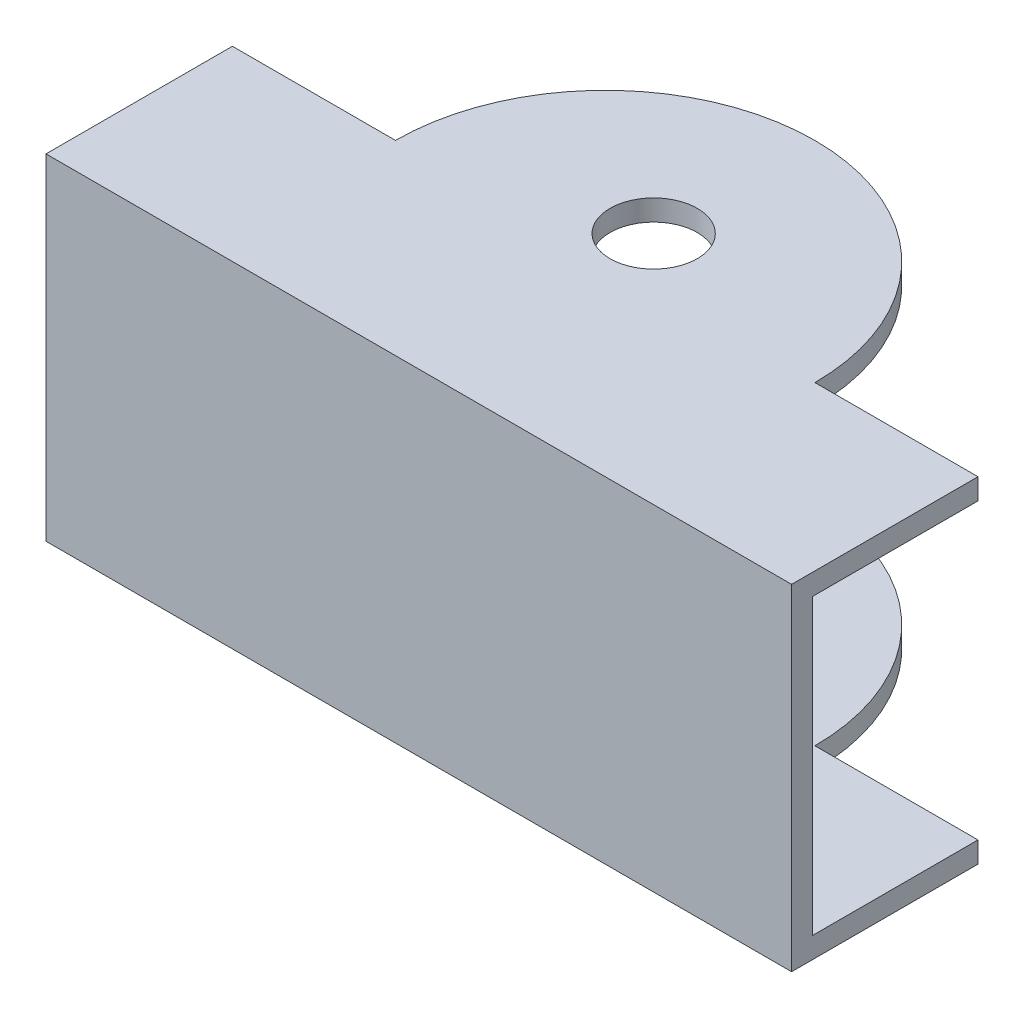
SolidWorks part; units mm, degrees
material "6061 Alloy"
ref_plane "Front Plane" through (0, 0, 0) normal (0, 0, 1) x (1, 0, 0)
ref_plane "Top Plane" through (0, 0, 0) normal (0, 1, 0) x (1, 0, 0)
ref_plane "Right Plane" through (0, 0, 0) normal (1, 0, 0) x (0, 0, -1)
sketch "Sketch1" plane through (0, 0, 0) normal (0, 1, 0) x (1, 0, 0)
  line L0 (0, 0) -> (28.2222, 0)
  line L1 (28.2222, 0) -> (28.2222, 14.1111)
  line L2 (28.2222, 14.1111) -> (15.875, 14.1111)
  line L3 (0, 0) -> (-28.2222, 0)
  line L4 (-28.2222, 0) -> (-28.2222, 14.1111)
  line L5 (-28.2222, 14.1111) -> (-15.875, 14.1111)
  arc A0 (-15.875, 14.1111) -> (15.875, 14.1111) centre (0, 14.1111) cw
  point P9 (0, 29.9861)
  dimension "D1" = 15.875
extrude "Boss-Extrude2" add sketch "Sketch1" along normal blind 25.4
sketch "Sketch3" plane through (28.2222, 0, 0) normal (1, 0, 0) x (0, 0, -1)
  line L0 (0, 25.4) -> (14.1111, 25.4) construction
  line L1 (1.5875, 23.8125) -> (62.6533, 23.8125)
  line L2 (1.5875, 23.8125) -> (1.5875, 1.5875)
  line L3 (1.5875, 1.5875) -> (62.6533, 1.5875)
  line L4 (62.6533, 23.8125) -> (62.6533, 1.5875)
  line L5 (0, 0) -> (14.1111, 0) construction
  line L6 (0, 25.4) -> (0, 0) construction
  dimension "D1" = 1.5875
  dimension "D2" = 1.5875
  dimension "D3" = 1.5875
extrude "Cut-Extrude2" cut sketch "Sketch3" against normal through all
sketch "Sketch4" plane through (0, 25.4, 0) normal (0, 1, 0) x (1, 0, 0)
  line L0 (-28.2222, 0) -> (28.2222, 0) construction
  circle A0 centre (0, 17.78) radius 3.302
  dimension "D1" = 17.78
  dimension "D2" = 6.604
extrude "Cut-Extrude3" cut sketch "Sketch4" against normal through all
ref_plane "Mid plane" through (0, 12.7, 0) normal (0, 1, 0) x (1, 0, 0)
